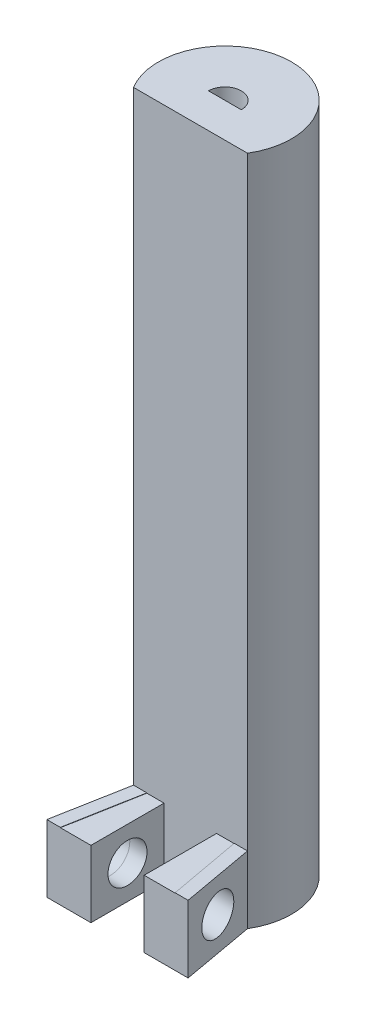
SolidWorks part; units mm, degrees
ref_plane "Front Plane" through (0, 0, 0) normal (0, 0, 1) x (1, 0, 0)
ref_plane "Top Plane" through (0, 0, 0) normal (0, 1, 0) x (1, 0, 0)
ref_plane "Right Plane" through (0, 0, 0) normal (1, 0, 0) x (0, 0, -1)
sketch "Sketch1" plane through (0, 0, 0) normal (0, 1, 0) x (1, 0, 0)
  circle A1 centre (0, 0) radius 12.6252
extrude "Boss-Extrude1" add sketch "Sketch1" against normal blind 127.254 contours A1
sketch "Sketch2" plane through (0, -127.254, 0) normal (0, -1, 0) x (-1, 0, 0)
  line L0 (-10.8004, -6.538) -> (10.8004, -6.538)
  line L1 (10.8004, -6.538) -> (10.8004, -12.6252)
  line L2 (10.8004, -12.6252) -> (-10.8004, -12.6252)
  line L3 (-10.8004, -12.6252) -> (-10.8004, -6.538)
  circle A0 centre (0, 0) radius 12.6252 construction
extrude "Cut-Extrude1" cut sketch "Sketch2" against normal blind 155.702
sketch "Sketch3" plane through (0, -127.254, 0) normal (0, -1, 0) x (-1, 0, 0)
  line L0 (3.1262, 0) -> (-3.0916, 0)
  arc A1 (-3.0916, 0) -> (3.1262, 0) centre (0.0173, 0) cw
extrude "Cut-Extrude2" cut sketch "Sketch3" against normal blind 141.0817
sketch "Sketch4" plane through (0, -127.254, 0) normal (0, -1, 0) x (1, 0, 0)
  line L0 (-10.8004, 6.538) -> (-8.2748, 6.538)
  line L1 (-10.8004, 6.538) -> (10.8004, 6.538) construction
  line L2 (-8.2748, 6.538) -> (-10.8004, 20.3961)
  line L3 (-10.8004, 20.3961) -> (-13.3646, 20.3961)
  line L4 (-13.3646, 20.3961) -> (-10.8004, 6.538)
  line L5 (10.8004, 6.538) -> (8.2919, 6.538)
  line L6 (8.2919, 6.538) -> (10.8004, 20.3961)
  line L7 (10.8004, 20.3961) -> (13.2794, 20.3961)
  line L8 (13.2794, 20.3961) -> (10.8004, 6.538)
extrude "Boss-Extrude2" add sketch "Sketch4" against normal blind 12.7552 contours L4 L0 L2 L3
sketch "Sketch5" plane through (0, -127.254, 0) normal (0, -1, 0) x (1, 0, 0)
  line L0 (10.8004, 6.538) -> (8.2879, 6.538)
  line L1 (-8.2748, 6.538) -> (10.8004, 6.538) construction
  line L2 (8.2879, 6.538) -> (10.8004, 20.2585)
  line L3 (10.8004, 20.2585) -> (13.2656, 20.2585)
  line L4 (13.2656, 20.2585) -> (10.8004, 6.538)
extrude "Boss-Extrude3" add sketch "Sketch5" against normal blind 12.7552
sketch "Sketch9" plane through (0, -127.254, 0) normal (0, -1, 0) x (-1, 0, 0)
  line L1 (10.8004, -20.3961) -> (8.2748, -20.3961)
  line L2 (8.2748, -20.3961) -> (8.2748, -6.538)
  line L9 (-10.8004, -6.538) -> (-13.2656, -20.2585)
  line L10 (-13.2656, -20.2585) -> (-10.8004, -20.2585)
  line L11 (-10.8004, -20.2585) -> (-8.2879, -6.538)
  line L12 (-8.2879, -6.538) -> (8.2748, -6.538)
  line L13 (8.2748, -6.538) -> (10.8004, -20.3961)
  line L14 (10.8004, -20.3961) -> (13.3646, -20.3961)
  line L15 (13.3646, -20.3961) -> (10.8004, -6.538)
  line L20 (8.2748, -6.538) -> (10.8004, -20.3961)
  arc A1 (10.8004, -6.538) -> (-10.8004, -6.538) centre (0, 0) ccw
  dimension "D1" = 0
extrude "Boss-Extrude4" add sketch "Sketch9" against normal blind 12.7
sketch "Sketch10" plane through (0, -127.254, 0) normal (0, -1, 0) x (-1, 0, 0)
  line L1 (-8.2879, -6.538) -> (-8.2879, -20.2585)
  line L2 (-8.2879, -20.2585) -> (-10.8004, -20.2585)
  line L3 (-8.2879, -6.538) -> (-10.8004, -20.2585)
extrude "Boss-Extrude5" add sketch "Sketch10" against normal blind 12.7 contours L2 L1 L3
sketch "Sketch11" plane through (8.2879, 0, 0) normal (-1, 0, 0) x (0, 0, 1)
  circle A0 centre (13.3982, -120.904) radius 3.689
extrude "Cut-Extrude3" cut sketch "Sketch11" against normal blind 13.97 contours A0
sketch "Sketch12" plane through (-8.2748, 0, 0) normal (1, 0, 0) x (0, 0, -1)
  circle A0 centre (-13.467, -120.904) radius 3.8015
extrude "Cut-Extrude4" cut sketch "Sketch12" against normal blind 11.43 contours A0
sketch "Sketch13" plane through (0, -127.254, 0) normal (0, -1, 0) x (1, 0, 0)
  line L0 (8.2879, 20.2585) -> (4.9404, 20.2585)
  line L1 (4.9404, 20.2585) -> (4.9404, 6.538)
  line L2 (-8.2748, 6.538) -> (8.2879, 6.538) construction
  line L3 (4.9404, 6.538) -> (8.2879, 6.538)
  line L4 (8.2879, 6.538) -> (8.2879, 20.2585)
extrude "Boss-Extrude6" add sketch "Sketch13" against normal blind 12.7 contours L4 L0 L1 L3
sketch "Sketch14" plane through (0, 0, 20.3961) normal (0, 0, 1) x (1, 0, 0)
  line L0 (-8.2748, -114.554) -> (-5.0099, -114.554)
  line L1 (-5.0099, -114.554) -> (-5.0099, -127.254)
  line L2 (-8.2748, -127.254) -> (4.9404, -127.254) construction
  line L3 (-5.0099, -127.254) -> (-8.2748, -127.254)
  line L4 (-8.2748, -127.254) -> (-8.2748, -114.554)
extrude "Boss-Extrude7" add sketch "Sketch14" against normal blind 13.97 contours L4 L0 L1 L3
sketch "Sketch15" plane through (-9.2732, 0, -1.7159) normal (-0.9833, 0, -0.1819) x (-0.1819, 0, 0.9833)
  circle A0 centre (15.4406, -120.904) radius 3.866
sketch "Sketch16" plane through (4.9404, 0, 0) normal (-1, 0, 0) x (0, 0, 1)
  circle A0 centre (13.3982, -120.904) radius 3.6945
extrude "Cut-Extrude6" cut sketch "Sketch16" against normal blind 45.212 contours A0
sketch "Sketch17" plane through (-5.0099, 0, 0) normal (1, 0, 0) x (0, 0, -1)
  circle A0 centre (-13.467, -120.904) radius 3.7002
extrude "Cut-Extrude7" cut sketch "Sketch17" against normal blind 28.702 contours A0
